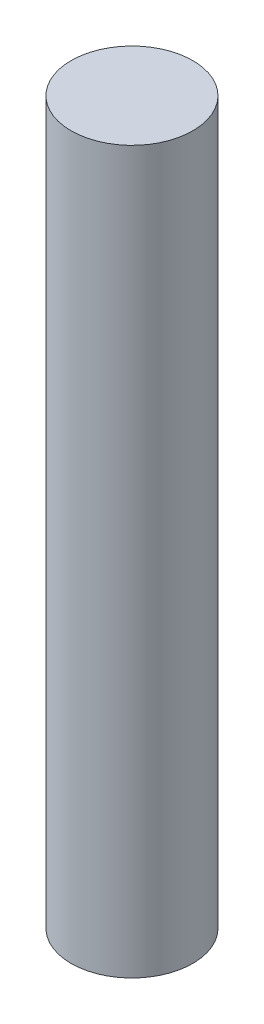
SolidWorks part; units mm, degrees
ref_plane "前视基准面" through (0, 0, 0) normal (0, 0, 1) x (1, 0, 0)
ref_plane "上视基准面" through (0, 0, 0) normal (0, 1, 0) x (1, 0, 0)
ref_plane "右视基准面" through (0, 0, 0) normal (1, 0, 0) x (0, 0, -1)
other "Configuration Table"
sketch "草图1" plane through (0, 0, 0) normal (0, 1, 0) x (1, 0, 0)
  circle A0 centre (0, 0) radius 1.35
  dimension "D1" = 2.7
extrude "凸台-拉伸1" add sketch "草图1" along normal blind 16
